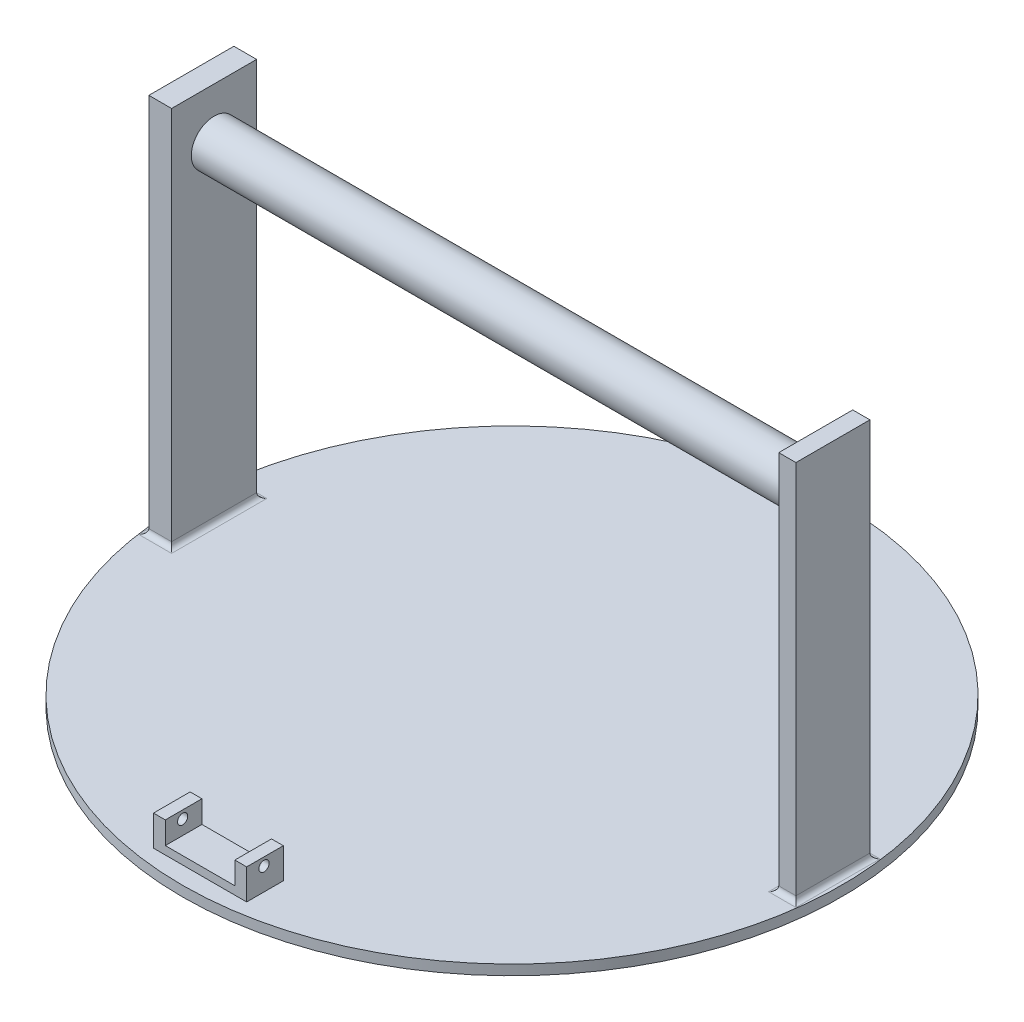
SolidWorks part; units mm, degrees
ref_plane "Front Plane" through (0, 0, 0) normal (0, 0, 1) x (1, 0, 0)
ref_plane "Top Plane" through (0, 0, 0) normal (0, 1, 0) x (1, 0, 0)
ref_plane "Right Plane" through (0, 0, 0) normal (1, 0, 0) x (0, 0, -1)
sketch "Sketch1" plane through (0, 0, 0) normal (0, 1, 0) x (1, 0, 0)
  circle A0 centre (0, 0) radius 650
  dimension "D1" = 1300
extrude "Boss-Extrude1" add sketch "Sketch1" along normal blind 20
sketch "Sketch2" plane through (0, 20, 0) normal (0, 1, 0) x (1, 0, 0)
  line L0 (-650, 0) -> (650, 0)
  line L2 (-632.4038, -83.8567) -> (-587.5449, -83.8567)
  line L3 (-632.4038, -83.8567) -> (-632.4038, 83.8567)
  line L4 (-632.4038, 83.8567) -> (-587.5449, 83.8567)
  line L5 (-587.5449, -83.8567) -> (-587.5449, 83.8567)
  line L6 (-632.4038, -83.8567) -> (-587.5449, 83.8567) construction
  line L7 (-632.4038, 83.8567) -> (-587.5449, -83.8567) construction
  line L8 (599.0743, -72.9581) -> (632.9337, -72.9581)
  line L9 (599.0743, -72.9581) -> (599.0743, 72.9581)
  line L10 (599.0743, 72.9581) -> (632.9337, 72.9581)
  line L11 (632.9337, -72.9581) -> (632.9337, 72.9581)
  line L12 (599.0743, -72.9581) -> (632.9337, 72.9581) construction
  line L13 (599.0743, 72.9581) -> (632.9337, -72.9581) construction
  circle A0 centre (0, 0) radius 650 construction
  point P0 (-609.9743, 0)
  point P7 (0, 0)
  point P13 (616.004, 0)
extrude "Boss-Extrude2" add sketch "Sketch2" along normal blind 750 contours L8 L11 L0 L9 | L0 L11 L10 L9 | L2 L5 L0 L3 | L0 L5 L4 L3
sketch "Sketch3" plane through (-587.5449, 0, 0) normal (1, 0, 0) x (0, 0, -1)
  line L0 (-83.8567, 20) -> (83.8567, 20) construction
  circle A0 centre (0, 670) radius 45
  dimension "D1" = 650
  dimension "D2" = 90
extrude "Boss-Extrude3" add sketch "Sketch3" along normal up to surface (1186.6192 mm away) up to face at (599.0743, 395, 0)
fillet "Fillet1" radius 10 8 edges at (616.004, 20, -72.9581) (632.9337, 20, 0) (616.004, 20, 72.9581) (599.0743, 20, 0) (-609.9743, 20, -83.8567) (-632.4038, 20, 0) (-609.9743, 20, 83.8567) (-587.5449, 20, 0)
sketch "Sketch4" plane through (0, 20, 0) normal (0, 1, 0) x (1, 0, 0)
  line L1 (-91.8907, -615.2106) -> (91.8907, -615.2106)
  line L2 (-91.8907, -615.2106) -> (-91.8907, -542.9394)
  line L3 (-91.8907, -542.9394) -> (91.8907, -542.9394)
  line L4 (91.8907, -615.2106) -> (91.8907, -542.9394)
  line L5 (-91.8907, -615.2106) -> (91.8907, -542.9394) construction
  line L6 (-91.8907, -542.9394) -> (91.8907, -615.2106) construction
  point P0 (0, -579.075)
extrude "Boss-Extrude4" add sketch "Sketch4" along normal blind 60
sketch "Sketch5" plane through (0, 0, 615.2106) normal (0, 0, 1) x (1, 0, 0)
  line L0 (-91.8907, 80) -> (91.8907, 80) construction
  line L1 (-68.5813, 123.9239) -> (68.5813, 123.9239)
  line L2 (-68.5813, 123.9239) -> (-68.5813, 36.0761)
  line L3 (-68.5813, 36.0761) -> (68.5813, 36.0761)
  line L4 (68.5813, 123.9239) -> (68.5813, 36.0761)
  line L5 (-68.5813, 123.9239) -> (68.5813, 36.0761) construction
  line L6 (-68.5813, 36.0761) -> (68.5813, 123.9239) construction
  point P0 (0, 80)
extrude "Cut-Extrude1" cut sketch "Sketch5" against normal blind 139
sketch "Sketch6" plane through (91.8907, 0, 0) normal (1, 0, 0) x (0, 0, -1)
  circle A0 centre (-581.0154, 64.2972) radius 10.0589
extrude "Cut-Extrude2" cut sketch "Sketch6" against normal blind 200
